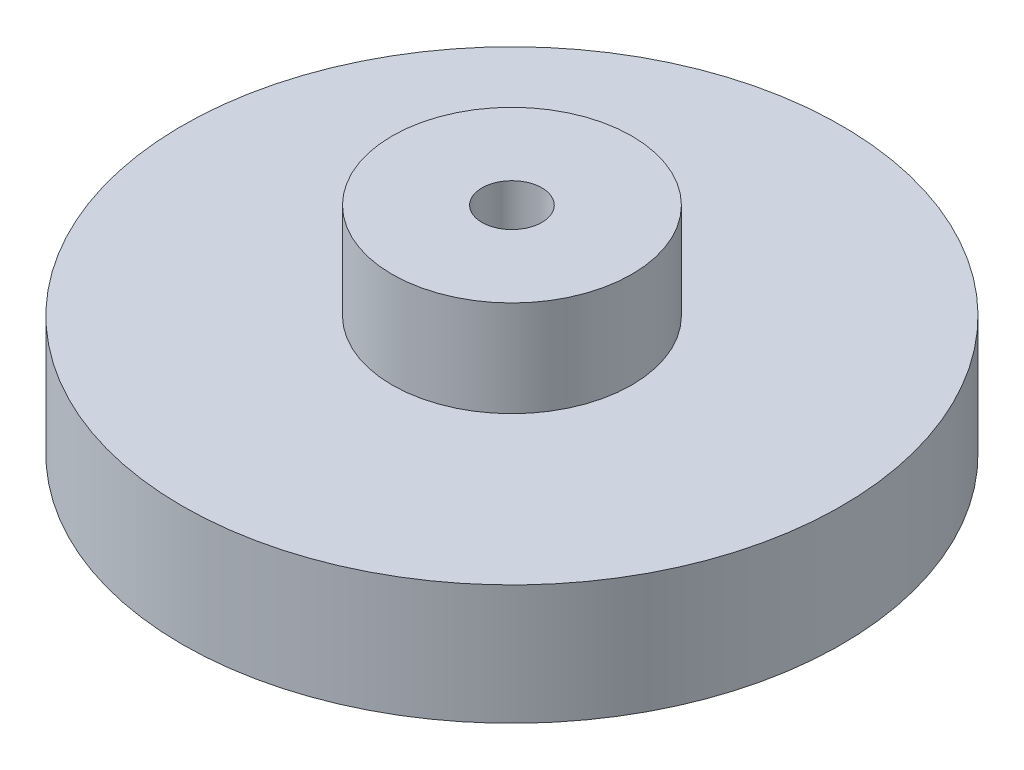
SolidWorks part; units mm, degrees
ref_plane "Alzado" through (0, 0, 0) normal (0, 0, 1) x (1, 0, 0)
ref_plane "Planta" through (0, 0, 0) normal (0, 1, 0) x (1, 0, 0)
ref_plane "Vista lateral" through (0, 0, 0) normal (1, 0, 0) x (0, 0, -1)
sketch "Croquis1" plane through (0, 0, 0) normal (0, 1, 0) x (1, 0, 0)
  circle A0 centre (0, 0) radius 27.5
  dimension "D1" = 55
extrude "Saliente-Extruir1" add sketch "Croquis1" along normal blind 10
sketch "Croquis2" plane through (0, 10, 0) normal (0, 1, 0) x (1, 0, 0)
  circle A0 centre (0, 0) radius 10
  dimension "D1" = 20
extrude "Saliente-Extruir2" add sketch "Croquis2" along normal blind 8
sketch "Croquis3" plane through (0, 18, 0) normal (0, 1, 0) x (1, 0, 0)
  circle A0 centre (0, 0) radius 2.5
  dimension "D1" = 5
extrude "Cortar-Extruir1" cut sketch "Croquis3" against normal up to next
